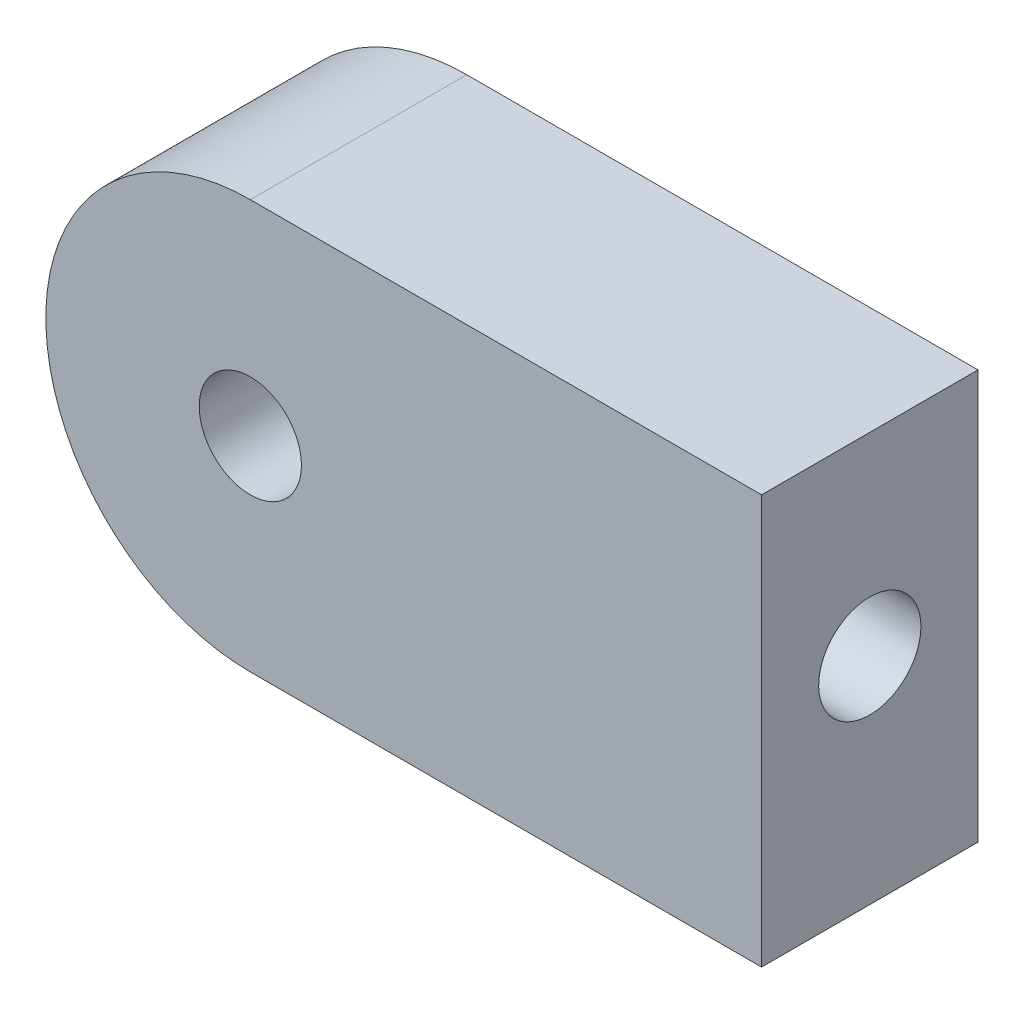
SolidWorks part; units mm, degrees
ref_plane "Plan de face" through (0, 0, 0) normal (0, 0, 1) x (1, 0, 0)
ref_plane "Plan de dessus" through (0, 0, 0) normal (0, 1, 0) x (1, 0, 0)
ref_plane "Plan de droite" through (0, 0, 0) normal (1, 0, 0) x (0, 0, -1)
sketch "Esquisse2" plane through (0, 0, 0) normal (0, 0, 1) x (1, 0, 0)
  line L0 (0, 6) -> (15, 6)
  line L1 (15, 6) -> (15, -6)
  line L2 (15, -6) -> (0, -6)
  arc A0 (0, -6) -> (0, 6) centre (0, 0) cw
  point P5 (0, 0)
  dimension "D2" = 6
  dimension "D1" = 15
extrude "Boss.-Extru.1" add sketch "Esquisse2" along normal blind 6.35
sketch "Esquisse3" plane through (15, 0, 0) normal (1, 0, 0) x (0, 0, -1)
  line L0 (-6.35, -6) -> (-6.35, 6) construction
  circle A0 centre (-3.175, 0.3189) radius 1.5
  dimension "D1" = 3
  dimension "D2" = 3.175
extrude "Enlèv. mat.-Extru.1" cut sketch "Esquisse3" against normal blind 6.35
sketch "Esquisse4" plane through (0, 0, 6.35) normal (0, 0, 1) x (1, 0, 0)
  circle A0 centre (0, 0) radius 1.5
  dimension "D1" = 3
extrude "Enlèv. mat.-Extru.2" cut sketch "Esquisse4" against normal blind 6.35
